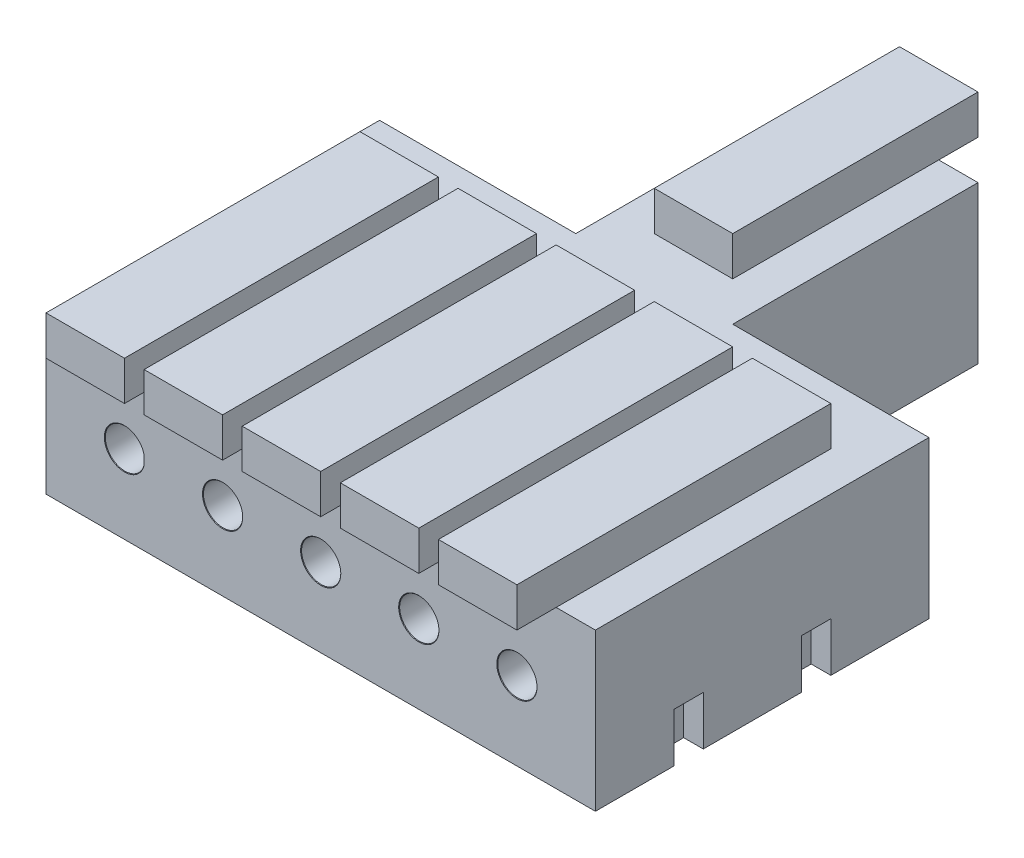
SolidWorks part; units mm, degrees
material "ABS"
ref_plane "Front Plane" through (0, 0, 0) normal (0, 0, 1) x (1, 0, 0)
ref_plane "Top Plane" through (0, 0, 0) normal (0, 1, 0) x (1, 0, 0)
ref_plane "Right Plane" through (0, 0, 0) normal (1, 0, 0) x (0, 0, -1)
sketch "Sketch1" plane through (0, 0, 0) normal (0, 1, 0) x (1, 0, 0)
  line L1 (0, 0) -> (8, 0)
  line L2 (0, 0) -> (0, 17)
  line L3 (0, 17) -> (8, 17)
  line L4 (8, 0) -> (8, 17)
  dimension "D1" = 8
  dimension "D2" = 17
extrude "connector_body" add sketch "Sketch1" along normal blind 8
sketch "Sketch2" plane through (0, 0, 0) normal (0, 0, -1) x (-1, 0, 0)
  line L0 (0, 8) -> (0, 0) construction
  line L1 (-8, 8) -> (0, 8) construction
  point P0 (-4, 4)
  dimension "D1" = 4
  dimension "D2" = 4
hole_wizard "cable_hole" positions "Sketch2" profile "Sketch3" hole size "Ø2.0" standard "DIN"
sketch "Sketch3" plane through (4, 4, 0) normal (1, 0, 0) x (0, -1, 0)
  line L0 (0, 0) -> (0, 10.6009)
  line L1 (0, 10.6009) -> (1, 10)
  line L2 (1, 10) -> (1, 0.025)
  line L3 (1, 0.025) -> (1.025, 0)
  line L5 (1.025, 0) -> (0, 0)
  line L6 (-1, 0.025) -> (-1.025, 0) construction
  line L10 (0, 10.6009) -> (-1, 10) construction
  line L11 (0, -6.35) -> (0, 107.95) construction
  dimension "Hole Dia." = 2
  dimension "Hole Depth" = 10
  dimension "Near C'Sink Dia." = 2.05
  dimension "Near C'Sink Angle" = 90
  dimension "Drill Angle" = 118
sketch "Sketch4" plane through (0, 8, 0) normal (0, 1, 0) x (1, 0, 0)
  line L0 (8, 0) -> (8, 17) construction
  line L1 (2, 14) -> (6, 14)
  line L2 (2, 14) -> (2, -2)
  line L3 (2, -2) -> (6, -2)
  line L4 (6, 14) -> (6, -2)
  line L6 (8, 17) -> (0, 17) construction
  dimension "D1" = 4
  dimension "D2" = 2
  dimension "D3" = 3
  dimension "D4" = 16
extrude "clamp" add sketch "Sketch4" along normal blind 2
pattern_linear "connector_pattern" count 5 spacing 5 along (1, 0, 0) of "connector_body", "cable_hole", "clamp"
sketch "Sketch5" plane through (0, 8, 0) normal (0, 1, 0) x (1, 0, 0)
  line L0 (28, 17) -> (0, 17) construction
  line L1 (10, 17) -> (18, 17)
  line L2 (10, 17) -> (10, 29.5)
  line L3 (10, 29.5) -> (18, 29.5)
  line L4 (18, 17) -> (18, 29.5)
  line L5 (0, 17) -> (0, 0) construction
  dimension "D1" = 8
  dimension "D2" = 10
  dimension "D3" = 12.5
extrude "single_body" add sketch "Sketch5" against normal up to vertex (8 mm away)
sketch "Sketch6" plane through (0, 0, 0) normal (-1, 0, 0) x (0, 0, 1)
  line L0 (-17, 0) -> (0, 0) construction
  line L1 (-12, 0) -> (-10.5, 0)
  line L2 (-12, 0) -> (-12, 2.5004)
  line L3 (-12, 2.5004) -> (-10.5, 2.5004)
  line L4 (-10.5, 0) -> (-10.5, 2.5004)
  line L5 (-17, 0) -> (-17, 8) construction
  line L6 (-5.5, 0) -> (-4, 0)
  line L7 (-5.5, 0) -> (-5.5, 2.5004)
  line L8 (-5.5, 2.5004) -> (-4, 2.5004)
  line L9 (-4, 0) -> (-4, 2.5004)
  point P12 (-4.75, 0)
  dimension "D1" = 5
  dimension "D2" = 1.5
  dimension "D3" = 1.5
  dimension "D4" = 2.5004
  dimension "D5" = 5
extrude "chaining_nobs" add sketch "Sketch6" along normal blind 1
sketch "Sketch7" plane through (0, 0, 0) normal (0, -1, 0) x (1, 0, 0)
  line L1 (28, -4) -> (27, -4)
  line L2 (28, -4) -> (28, -5.5)
  line L3 (28, -5.5) -> (27, -5.5)
  line L4 (27, -4) -> (27, -5.5)
  line L5 (-1, -10.5) -> (0, -10.5) construction
  line L6 (27, -12) -> (28, -12)
  line L7 (27, -12) -> (27, -10.5)
  line L8 (27, -10.5) -> (28, -10.5)
  line L9 (28, -12) -> (28, -10.5)
  line L10 (28, 0) -> (28, -17) construction
  line L11 (-1, -5.5) -> (0, -5.5) construction
  point P12 (0, 0)
  point P15 (0, 0)
  dimension "D1" = 1
  dimension "D2" = 1.5
sketch "Sketch8" plane through (0, 8, 0) normal (0, 1, 0) x (1, 0, 0)
  line L0 (10, 29.5) -> (10, 17) construction
  line L1 (12, 19) -> (16, 19)
  line L2 (12, 19) -> (12, 31.5)
  line L3 (12, 31.5) -> (16, 31.5)
  line L4 (16, 19) -> (16, 31.5)
  line L5 (28, 17) -> (18, 17) construction
  line L6 (18, 29.5) -> (10, 29.5) construction
  dimension "D1" = 4
  dimension "D2" = 2
  dimension "D3" = 2
  dimension "D4" = 2
extrude "chaining_nobs_cutout" cut sketch "Sketch7" against normal up to vertex (2.5004 mm away)
extrude "single_body_clamp" add sketch "Sketch8" along normal up to vertex (2 mm away)
sketch "Sketch9" plane through (0, 0, 0) normal (0, -1, 0) x (1, 0, 0)
  line L1 (10, -29.5) -> (10, -17) construction
  line L2 (18, -29.5) -> (10, -29.5) construction
  circle A0 centre (8, -19) radius 2.25
  circle A1 centre (8, -19) radius 1.5
  circle A2 centre (20, -19) radius 1.5
  circle A3 centre (20, -19) radius 2.25
  dimension "D2" = 2
  dimension "D3" = 4.5
  dimension "D4" = 3
  dimension "D1" = 12
  dimension "D5" = 10.5
extrude "mounting_rings" add sketch "Sketch9" against normal blind 2
